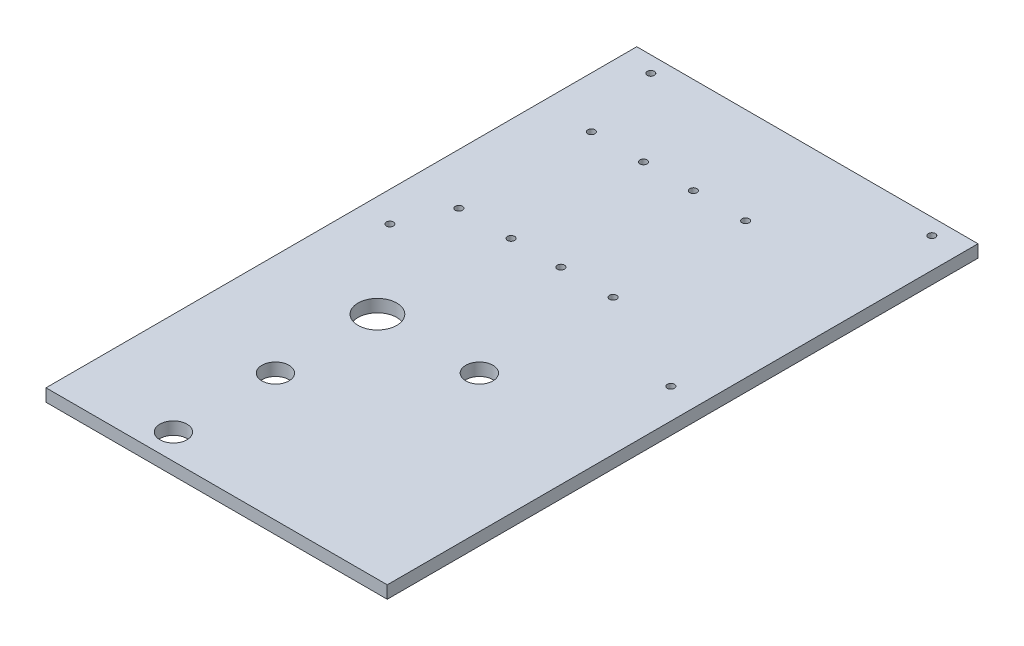
SolidWorks part; units mm, degrees
ref_plane "Front Plane" through (0, 0, 0) normal (0, 0, 1) x (1, 0, 0)
ref_plane "Top Plane" through (0, 0, 0) normal (0, 1, 0) x (1, 0, 0)
ref_plane "Right Plane" through (0, 0, 0) normal (1, 0, 0) x (0, 0, -1)
sketch "Sketch1" plane through (0, 0, 0) normal (0, 1, 0) x (1, 0, 0)
  line L0 (50.8, 57.15) -> (25.4, 57.15) construction
  line L1 (0, 0) -> (85, 0)
  line L2 (0, 0) -> (0, 147.15)
  line L3 (0, 147.15) -> (85, 147.15)
  line L4 (85, 0) -> (85, 147.15)
  line L5 (25.4, 57.15) -> (25.4, 31.75) construction
  line L6 (25.4, 31.75) -> (25.4, 6.35) construction
  line L7 (38.1, 90.15) -> (51.1, 90.15) construction
  line L8 (7.5, 143.15) -> (77.5, 143.15) construction
  line L9 (7.5, 143.15) -> (7.5, 78.15) construction
  line L10 (7.5, 78.15) -> (77.5, 78.15) construction
  line L11 (77.5, 143.15) -> (77.5, 78.15) construction
  line L12 (12.7, 123.15) -> (25.7, 123.15) construction
  line L13 (12.7, 123.15) -> (12.7, 90.15) construction
  line L14 (12.7, 90.15) -> (25.7, 90.15) construction
  line L15 (25.7, 123.15) -> (25.7, 90.15) construction
  line L16 (51.1, 123.15) -> (51.1, 90.15) construction
  line L17 (38.1, 123.15) -> (51.1, 123.15) construction
  line L18 (38.1, 123.15) -> (38.1, 90.15) construction
  circle A0 centre (25.4, 57.15) radius 4.826
  circle A1 centre (25.4, 31.75) radius 3.38
  circle A2 centre (25.4, 6.35) radius 3.38
  circle A3 centre (50.8, 57.15) radius 3.38
  circle A4 centre (7.5, 143.15) radius 0.889
  circle A5 centre (77.5, 143.15) radius 0.889
  circle A6 centre (77.5, 78.15) radius 0.889
  circle A7 centre (7.5, 78.15) radius 0.889
  circle A8 centre (12.7, 123.15) radius 0.889
  circle A9 centre (25.7, 90.15) radius 0.889
  circle A10 centre (25.7, 123.15) radius 0.889
  circle A11 centre (12.7, 90.15) radius 0.889
  circle A12 centre (38.1, 123.15) radius 0.889
  circle A13 centre (51.1, 123.15) radius 0.889
  circle A14 centre (51.1, 90.15) radius 0.889
  circle A15 centre (38.1, 90.15) radius 0.889
  dimension "D2" = 9.652
  dimension "D7" = 6.76
  dimension "D12" = 1.778
  dimension "D1" = 25.4
  dimension "D3" = 6.35
  dimension "D4" = 25.4
  dimension "D5" = 90
  dimension "D6" = 85
  dimension "D8" = 70
  dimension "D9" = 65
  dimension "D10" = 4
  dimension "D11" = 7.5
  dimension "D13" = 13
  dimension "D14" = 33
  dimension "D15" = 24
  dimension "D16" = 12.7
  dimension "D18" = 25.4
  dimension "D17" = 2
extrude "Boss-Extrude1" add sketch "Sketch1" along normal blind 3.125
